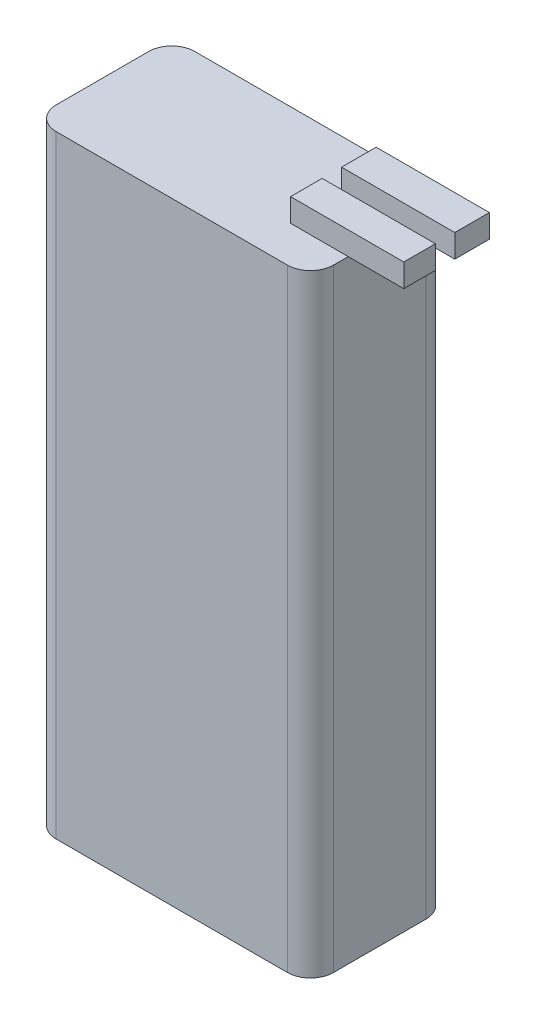
SolidWorks part; units mm, degrees
ref_plane "Front Plane" through (0, 0, 0) normal (0, 0, 1) x (1, 0, 0)
ref_plane "Top Plane" through (0, 0, 0) normal (0, 1, 0) x (1, 0, 0)
ref_plane "Right Plane" through (0, 0, 0) normal (1, 0, 0) x (0, 0, -1)
sketch "Sketch1" plane through (0, 0, 0) normal (0, 1, 0) x (1, 0, 0)
  line L1 (-10, 6) -> (10, 6)
  line L2 (-12, 4) -> (-12, -4)
  line L3 (-10, -6) -> (10, -6)
  line L4 (12, 4) -> (12, -4)
  line L5 (-12, 6) -> (12, -6) construction
  line L6 (-12, -6) -> (12, 6) construction
  arc A0 (12, -4) -> (10, -6) centre (10, -4) cw
  arc A1 (-12, 4) -> (-10, 6) centre (-10, 4) cw
  arc A2 (-10, -6) -> (-12, -4) centre (-10, -4) cw
  arc A3 (12, 4) -> (10, 6) centre (10, 4) ccw
  point P0 (0, 0)
  dimension "D3" = 2
  dimension "D1" = 24
  dimension "D2" = 12
extrude "Boss-Extrude1" add sketch "Sketch1" along normal blind 53
sketch "Sketch2" plane through (0, 53, 0) normal (0, 1, 0) x (1, 0, 0)
  line L1 (7.0112, 4.6726) -> (16.8041, 4.6726)
  line L2 (7.0112, 4.6726) -> (7.0112, 1.6795)
  line L3 (7.0112, 1.6795) -> (16.8041, 1.6795)
  line L4 (16.8041, 4.6726) -> (16.8041, 1.6795)
  line L5 (7.0112, 0) -> (16.8041, 0)
  line L6 (7.0112, 0) -> (7.0112, -2.7325)
  line L7 (7.0112, -2.7325) -> (16.8041, -2.7325)
  line L8 (16.8041, 0) -> (16.8041, -2.7325)
extrude "Boss-Extrude2" add sketch "Sketch2" along normal blind 2
